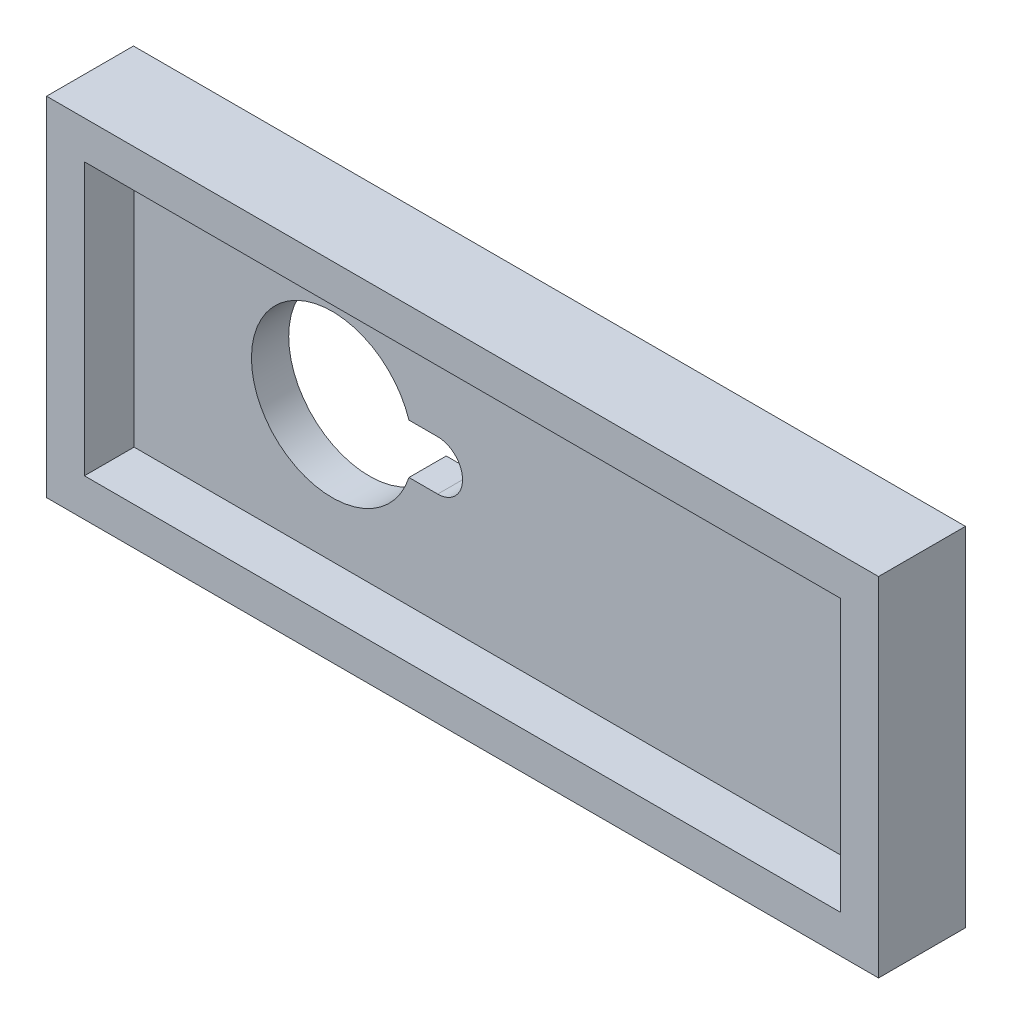
SolidWorks part; units mm, degrees
ref_plane "Alzado" through (0, 0, 0) normal (0, 0, 1) x (1, 0, 0)
ref_plane "Planta" through (0, 0, 0) normal (0, 1, 0) x (1, 0, 0)
ref_plane "Vista lateral" through (0, 0, 0) normal (1, 0, 0) x (0, 0, -1)
sketch "Croquis1" plane through (0, 0, 0) normal (0, 0, 1) x (1, 0, 0)
  line L1 (-73.5022, 31.681) -> (-6.5022, 31.681)
  line L2 (-73.5022, 31.681) -> (-73.5022, 3.681)
  line L3 (-73.5022, 3.681) -> (-6.5022, 3.681)
  line L4 (-6.5022, 31.681) -> (-6.5022, 3.681)
  dimension "D1" = 67
  dimension "D2" = 28
extrude "Saliente-Extruir1" add sketch "Croquis1" along normal blind 7
sketch "Croquis2" plane through (0, 0, 7) normal (0, 0, 1) x (1, 0, 0)
  line L0 (-6.5022, 31.681) -> (-73.5022, 31.681) construction
  line L1 (-70.4522, 28.631) -> (-9.5522, 28.631)
  line L2 (-70.4522, 28.631) -> (-70.4522, 6.731)
  line L3 (-70.4522, 6.731) -> (-9.5522, 6.731)
  line L4 (-9.5522, 28.631) -> (-9.5522, 6.731)
  line L5 (-73.5022, 3.681) -> (-6.5022, 3.681) construction
  line L6 (-73.5022, 31.681) -> (-73.5022, 3.681) construction
  line L7 (-6.5022, 3.681) -> (-6.5022, 31.681) construction
  dimension "D1" = 3.05
  dimension "D2" = 3.05
  dimension "D3" = 3.05
  dimension "D4" = 3.05
extrude "Cortar-Extruir1" cut sketch "Croquis2" against normal blind 4
sketch "Croquis3" plane through (0, 0, 0) normal (0, 0, -1) x (-1, 0, 0)
  line L1 (73.5022, 31.681) -> (73.5022, 3.681) construction
  circle A0 centre (46.0022, 17.681) radius 2
  circle A1 centre (54.5022, 17.681) radius 6.5
  dimension "D1" = 19
  dimension "D2" = 8.5
sketch "Croquis6" plane through (0, 0, 0) normal (0, 0, -1) x (-1, 0, 0)
  line L2 (46.0022, 15.681) -> (48.3175, 15.681)
  line L3 (46.0022, 19.681) -> (48.3175, 19.681)
  circle A0 centre (54.5022, 17.681) radius 6.5 construction
  arc A2 (46.0022, 15.681) -> (46.0022, 19.681) centre (46.0022, 17.681) cw
  arc A3 (48.3175, 15.681) -> (48.3175, 19.681) centre (54.5022, 17.681) ccw
extrude "Cortar-Extruir5" cut sketch "Croquis6" against normal up to vertex (3 mm away)
